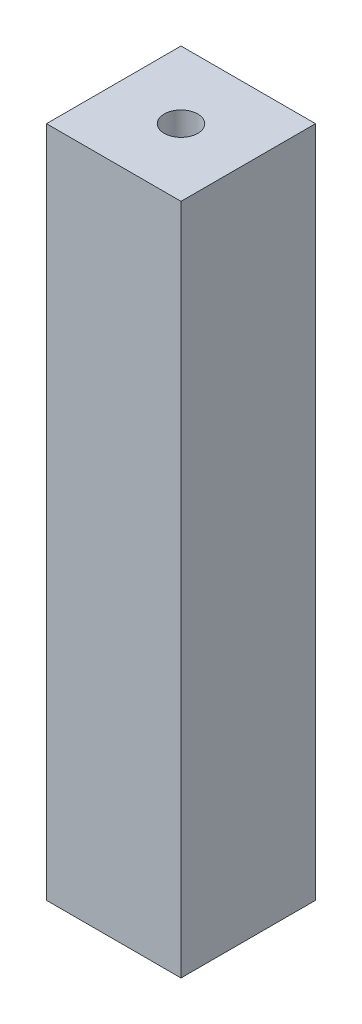
SolidWorks part; units mm, degrees
ref_plane "Front Plane" through (0, 0, 0) normal (0, 0, 1) x (1, 0, 0)
ref_plane "Top Plane" through (0, 0, 0) normal (0, 1, 0) x (1, 0, 0)
ref_plane "Right Plane" through (0, 0, 0) normal (1, 0, 0) x (0, 0, -1)
sketch "Sketch1" plane through (0, 0, 0) normal (0, 1, 0) x (1, 0, 0)
  line L1 (10, -10) -> (-10, -10)
  line L2 (10, -10) -> (10, 10)
  line L3 (10, 10) -> (-10, 10)
  line L4 (-10, -10) -> (-10, 10)
  line L5 (10, -10) -> (-10, 10) construction
  line L6 (10, 10) -> (-10, -10) construction
  point P0 (0, 0)
  dimension "D1" = 20
  dimension "D2" = 20
extrude "Boss-Extrude1" add sketch "Sketch1" along normal blind 100
sketch "Sketch2" plane through (0, 100, 0) normal (0, 1, 0) x (1, 0, 0)
  circle A0 centre (0, 0) radius 2.5
extrude "Cut-Extrude1" cut sketch "Sketch2" against normal blind 104
